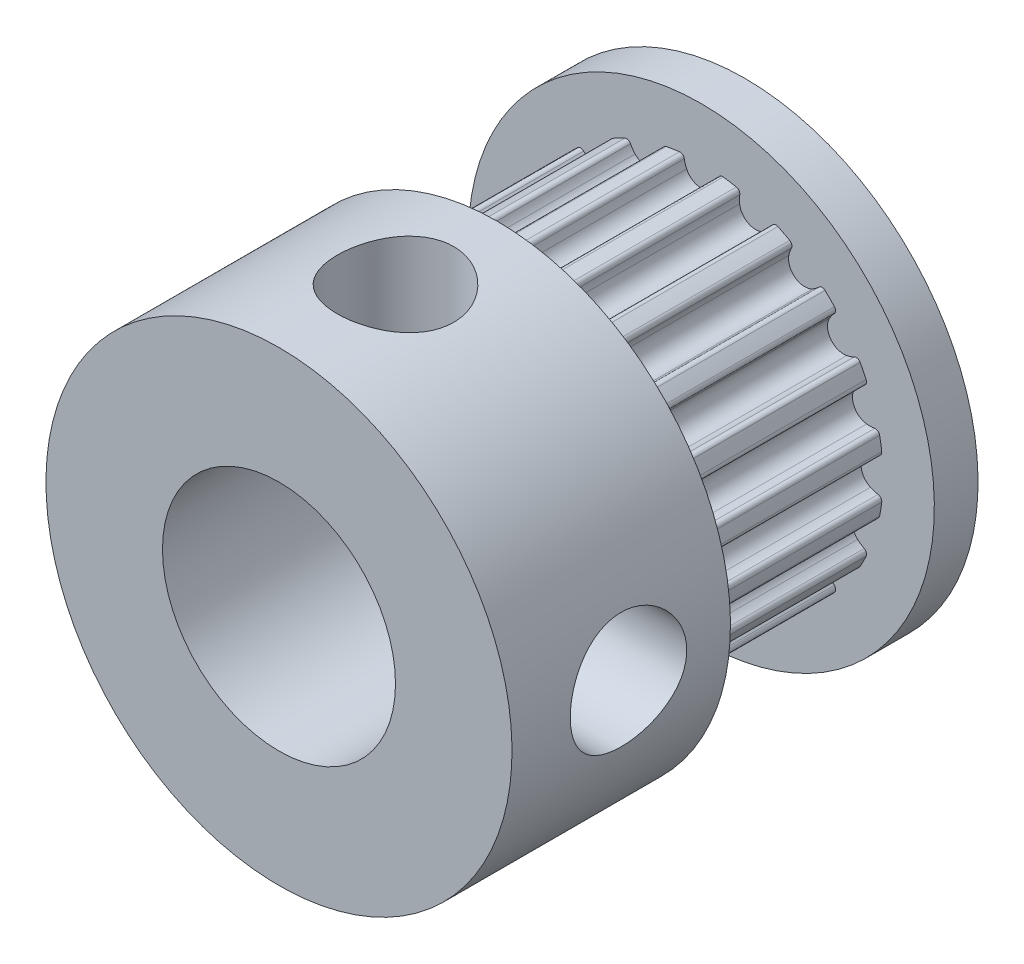
SolidWorks part; units mm, degrees
material "Aleación 6061"
ref_plane "Alzado" through (0, 0, 0) normal (0, 0, 1) x (1, 0, 0)
ref_plane "Planta" through (0, 0, 0) normal (0, 1, 0) x (1, 0, 0)
ref_plane "Vista lateral" through (0, 0, 0) normal (1, 0, 0) x (0, 0, -1)
sketch "Croquis1" plane through (0, 0, 0) normal (0, 0, 1) x (1, 0, 0)
  circle A0 centre (0, 0) radius 6.366
  dimension "D1" = 12.732
extrude "Saliente-Extruir1" add sketch "Croquis1" along normal blind 7
sketch "Croquis3" plane through (0, 0, 0) normal (0, 0, -1) x (-1, 0, 0)
  line L0 (0, 0) -> (0, 6.239) construction
  line L1 (0, 0) -> (0.976, 6.1622) construction
  line L2 (0.976, 6.1622) -> (0, 0) construction
  line L3 (0, 0) -> (-0.976, 6.1622) construction
  line L6 (0.976, 6.1622) -> (0.9959, 6.2876)
  line L8 (-0.976, 6.1622) -> (-0.9959, 6.2876)
  arc A0 (-0.7498, 6.1938) -> (-0.976, 6.1622) centre (0, 0) ccw
  arc A1 (-0.5037, 5.8059) -> (0.5037, 5.8059) centre (0, 6.039) ccw
  arc A2 (-0.5837, 6.0685) -> (-0.5037, 5.8059) centre (0.4038, 6.2259) ccw
  arc A3 (-0.5837, 6.0685) -> (-0.7498, 6.1938) centre (-0.7318, 6.0449) ccw
  arc A4 (0.5837, 6.0685) -> (0.5037, 5.8059) centre (-0.4038, 6.2259) cw
  arc A5 (0.5837, 6.0685) -> (0.7498, 6.1938) centre (0.7318, 6.0449) cw
  arc A6 (0.7498, 6.1938) -> (0.976, 6.1622) centre (0, 0) cw
  circle A7 centre (0, 0) radius 6.366 construction
  circle A11 centre (0, 0) radius 6.366
  circle M8 centre (0, 0) radius 6.366
  dimension "D1" = 6.239
  dimension "D4" = 1.11
  dimension "D5" = 2
  dimension "D7" = 0.3
  dimension "D3" = 18
  dimension "D6" = 0.2
extrude "Cortar-Extruir1" cut sketch "Croquis3" against normal through all contours A5 A6 L6 L8 A0 A3 A2 A1 A4 M8
pattern_circular "MatrizC1" count 20 over 360 about axis through (0, 0, 0) along (0, 0, 1) of "Cortar-Extruir1"
sketch "Croquis5" plane through (0, 0, 0) normal (1, 0, 0) x (0, 0, -1)
  line L0 (0, 0) -> (1.5, 0)
  line L1 (0, -0.5037) -> (0, 0.5037) construction
  line L2 (1.5, 0) -> (1.5, 8)
  line L3 (1.5, 8) -> (0, 8)
  line L4 (0, 8) -> (0, 0)
  line L5 (-7, 0) -> (-14.5, 0)
  line L6 (-7, 0.5037) -> (-7, -0.5037) construction
  line L7 (-14.5, 0) -> (-14.5, 8)
  line L8 (-14.5, 8) -> (-7, 8)
  line L10 (-7, 0) -> (-7, 8)
  point P12 (-6.9306, 6.9162)
  dimension "D1" = 8
  dimension "D2" = 1.5
  dimension "D3" = 8
  dimension "D4" = 7.5
revolve "Revolución1" add sketch "Croquis5" angle 360 about L5
sketch "Croquis6" plane through (0, 0, 14.5) normal (0, 0, 1) x (1, 0, 0)
  circle A0 centre (0, 0) radius 4
  dimension "D1" = 8
extrude "Cortar-Extruir2" cut sketch "Croquis6" against normal through all
sketch "Croquis8" plane through (0, 0, 0) normal (0, 1, 0) x (1, 0, 0)
  line L0 (-8, -7) -> (-8, -14.5) construction
  line L1 (0.5037, -7) -> (-0.5037, -7) construction
  circle A0 centre (0, -10.5) radius 2
  dimension "D1" = 4
  dimension "D2" = 8
  dimension "D3" = 3.5
extrude "Cortar-Extruir3" cut sketch "Croquis8" along normal through all
sketch "Croquis9" plane through (0, 0, 0) normal (1, 0, 0) x (0, 0, -1)
  line L0 (-14.5, -8) -> (-7, -8) construction
  line L3 (-7, -0.5037) -> (-7, 0.5037) construction
  circle A0 centre (-10.5, 0) radius 2
  point P4 (0, 0)
  point P6 (-7, -0.2463)
  point P7 (-10.2089, -0.2339)
  dimension "D1" = 4
  dimension "D2" = 8
  dimension "D3" = 3.5
extrude "Cortar-Extruir4" cut sketch "Croquis9" along normal through all
